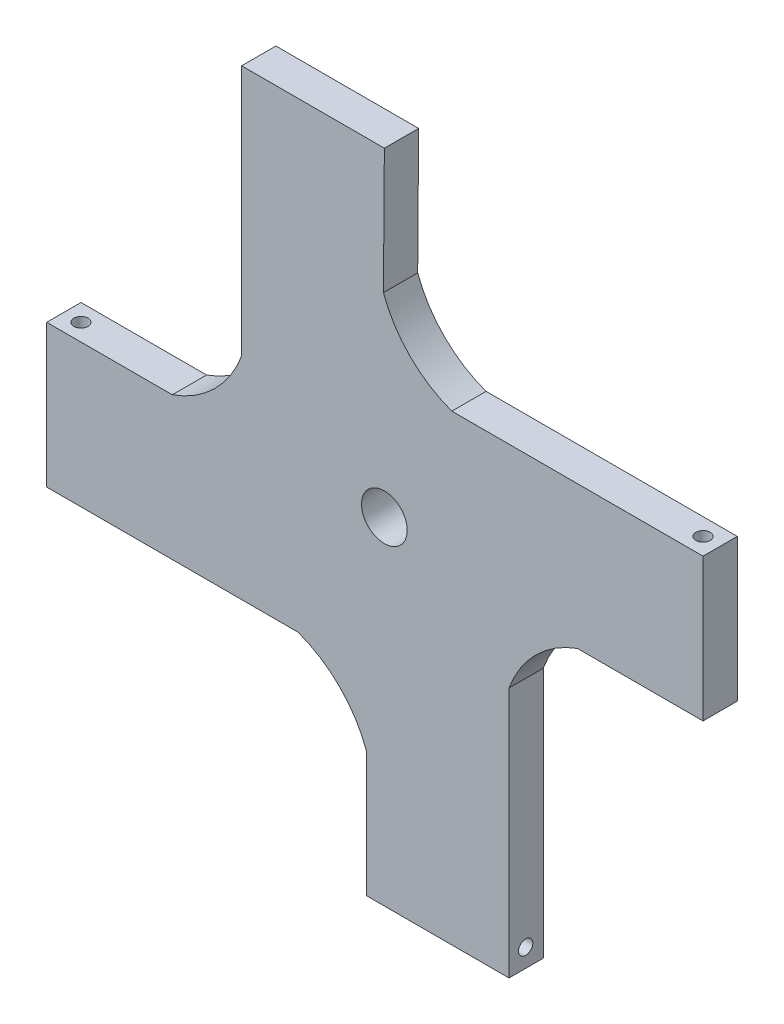
SolidWorks part; units mm, degrees
ref_plane "정면" through (0, 0, 0) normal (0, 0, 1) x (1, 0, 0)
ref_plane "윗면" through (0, 0, 0) normal (0, 1, 0) x (1, 0, 0)
ref_plane "우측면" through (0, 0, 0) normal (1, 0, 0) x (0, 0, -1)
sketch "스케치2" plane through (0, 0, 0) normal (0, 0, 1) x (1, 0, 0)
  line L0 (-102.5253, -57.6011) -> (-102.5253, -32.6011)
  line L1 (-68.3848, 23.378) -> (-43.3848, 23.378)
  line L2 (-68.3848, 23.378) -> (-68.3848, -20.622)
  line L3 (-46.5456, -91.5809) -> (-21.5456, -91.5809)
  line L4 (12.4342, -35.6011) -> (-9.5658, -35.6011)
  line L5 (12.4342, -35.6011) -> (12.4342, -10.6011)
  line L6 (-43.3848, 23.378) -> (-43.5456, 1.3786)
  line L7 (-102.5253, -57.6011) -> (-58.5253, -57.6011)
  line L8 (12.4342, -10.6011) -> (-31.5658, -10.6011)
  line L9 (-21.5456, -91.5809) -> (-21.5456, -47.5809)
  line L10 (-46.5456, -91.5809) -> (-46.5456, -69.5809)
  line L11 (-102.5253, -32.6011) -> (-80.5253, -32.6011)
  line L12 (-43.3848, 23.378) -> (-43.3848, -91.5809) construction
  line L14 (-102.5253, -32.6011) -> (12.4342, -32.6011) construction
  circle A0 centre (-43.3848, -32.6011) radius 4
  arc A2 (-31.5658, -10.6011) -> (-43.5456, 1.3786) centre (-24.7447, 8.1997) cw
  arc A3 (-9.5658, -35.6011) -> (-21.5456, -47.5809) centre (-2.7447, -54.402) ccw
  arc A4 (-58.5253, -57.6011) -> (-46.5456, -69.5809) centre (-65.3464, -76.402) cw
  arc A5 (-80.5253, -32.6011) -> (-68.3848, -20.622) centre (-87.1613, -13.7342) ccw
  point P0 (-43.3848, -32.6011)
  dimension "D3" = 25
  dimension "D4" = 22
  dimension "D8" = 20
  dimension "D10" = 20
  dimension "D12" = 20
  dimension "D16" = 59.1405
  dimension "D1" = 25
  dimension "D2" = 25
  dimension "D5" = 44
  dimension "D6" = 22
  dimension "D7" = 22
  dimension "D9" = 44
  dimension "D11" = 44
  dimension "D13" = 44
  dimension "D14" = 25
  dimension "D15" = 22
extrude "보스-돌출1" add sketch "스케치2" along normal blind 6
ref_plane "평면1" through (0, -57.6011, 0) normal (0, -1, 0) x (-1, 0, 0)
sketch "스케치3" plane through (0, -57.6011, 0) normal (0, -1, 0) x (-1, 0, 0)
  line L0 (102.5253, -3) -> (43.3853, -3) construction
  line L3 (102.5253, -6) -> (102.5253, 0) construction
  circle A0 centre (99.5253, -3) radius 1.25
  point P4 (99.5253, -3)
  dimension "D3" = 2.5
  dimension "D1" = 59.14
  dimension "D2" = 56.14
extrude "컷-돌출1" cut sketch "스케치3" against normal blind 5
ref_plane "평면2" through (0, -32.6011, 0) normal (0, 1, 0) x (1, 0, 0)
sketch "스케치4" plane through (0, -32.6011, 0) normal (0, 1, 0) x (1, 0, 0)
  circle A0 centre (-99.5253, -3) radius 1.25
  dimension "D1" = 2.5
extrude "컷-돌출2" cut sketch "스케치4" against normal blind 5
ref_plane "평면3" through (-21.5456, 0, 0) normal (1, 0, 0) x (0, 0, -1)
sketch "스케치5" plane through (-21.5456, 0, 0) normal (1, 0, 0) x (0, 0, -1)
  line L1 (-3.0876, -91.3478) -> (-3.0876, -32.2078) construction
  circle A1 centre (-3.0876, -88.3478) radius 1.25
  point P7 (-3.0876, -88.3478)
  dimension "D3" = 59.14
  dimension "D4" = 56.14
extrude "컷-돌출3" cut sketch "스케치5" against normal blind 5
ref_plane "평면4" through (-46.5456, 0, 0) normal (-1, 0, 0) x (0, 0, 1)
sketch "스케치6" plane through (-46.5456, 0, 0) normal (-1, 0, 0) x (0, 0, 1)
  circle A0 centre (3.0876, -88.3478) radius 1.25
extrude "컷-돌출4" cut sketch "스케치6" against normal blind 5
ref_plane "평면5" through (0, -10.6011, 0) normal (0, 1, 0) x (1, 0, 0)
sketch "스케치8" plane through (0, -10.6011, 0) normal (0, 1, 0) x (1, 0, 0)
  line L1 (12.4342, -3) -> (-46.7058, -3) construction
  line L2 (12.4342, -6) -> (12.4342, 0) construction
  circle A1 centre (9.4342, -3) radius 1.25
  point P9 (9.4342, -3)
  dimension "D3" = 59.14
  dimension "D4" = 56.14
extrude "컷-돌출5" cut sketch "스케치8" against normal blind 5
ref_plane "평면6" through (0, -35.6011, 0) normal (0, -1, 0) x (-1, 0, 0)
sketch "스케치9" plane through (0, -35.6011, 0) normal (0, -1, 0) x (-1, 0, 0)
  circle A0 centre (-9.4342, -3) radius 1.25
extrude "컷-돌출6" cut sketch "스케치9" against normal blind 5
